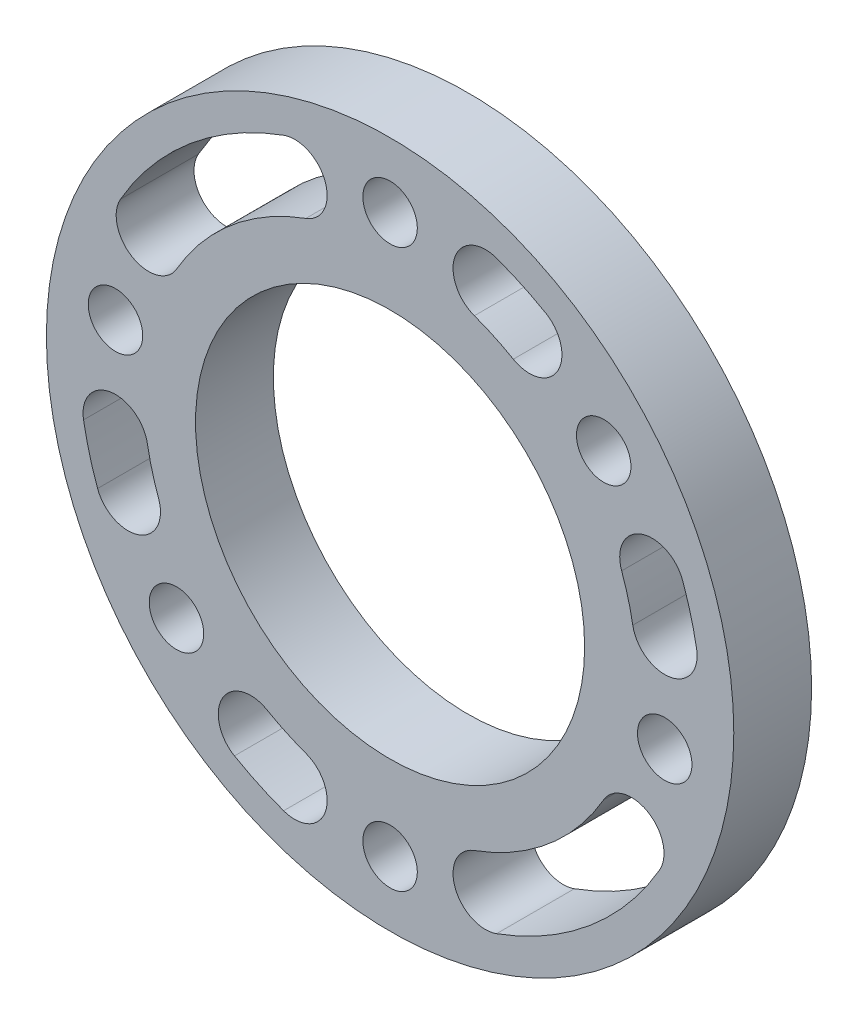
SolidWorks part; units mm, degrees
material "6061 合金"
ref_plane "前视基准面" through (0, 0, 0) normal (0, 0, 1) x (1, 0, 0)
ref_plane "上视基准面" through (0, 0, 0) normal (0, 1, 0) x (1, 0, 0)
ref_plane "右视基准面" through (0, 0, 0) normal (1, 0, 0) x (0, 0, -1)
sketch "草图1" plane through (0, 0, 0) normal (0, 0, 1) x (1, 0, 0)
  circle A0 centre (0, 0) radius 15
  circle A1 centre (0, 0) radius 26.5
  circle A2 centre (0, 0) radius 21.5 construction
  circle A3 centre (0, 21.5) radius 2.1
  circle A4 centre (16.47, 13.8199) radius 2.1
  circle A5 centre (21.1734, -3.7334) radius 2.1
  circle A6 centre (0, -21.5) radius 2.1
  circle A7 centre (-16.47, -13.8199) radius 2.1
  circle A8 centre (-21.1734, 3.7334) radius 2.1
  arc A9 (-18.6195, 10.75) -> (-7.3534, 20.2034) centre (0, 0) cw construction
  arc A10 (-8.2085, 22.5526) -> (-20.7846, 12) centre (0, 0) ccw
  arc A11 (-6.4984, 17.8542) -> (-16.4545, 9.5) centre (0, 0) ccw
  arc A12 (-6.4984, 17.8542) -> (-8.2085, 22.5526) centre (-7.3534, 20.2034) ccw
  arc A13 (-20.7846, 12) -> (-16.4545, 9.5) centre (-18.6195, 10.75) ccw
  arc A14 (7.3534, 20.2034) -> (10.75, 18.6195) centre (0, 0) cw construction
  arc A15 (12, 20.7846) -> (8.2085, 22.5526) centre (0, 0) ccw
  arc A16 (9.5, 16.4545) -> (6.4984, 17.8542) centre (0, 0) ccw
  arc A17 (9.5, 16.4545) -> (12, 20.7846) centre (10.75, 18.6195) ccw
  arc A18 (8.2085, 22.5526) -> (6.4984, 17.8542) centre (7.3534, 20.2034) ccw
  arc A19 (18.7113, 3.2993) -> (17.8542, 6.4984) centre (0, 0) ccw
  arc A20 (18.7113, 3.2993) -> (23.6354, 4.1676) centre (21.1734, 3.7334) ccw
  arc A21 (22.5526, 8.2085) -> (17.8542, 6.4984) centre (20.2034, 7.3534) ccw
  arc A22 (23.6354, 4.1676) -> (22.5526, 8.2085) centre (0, 0) ccw
  arc A23 (20.2034, 7.3534) -> (21.1734, 3.7334) centre (0, 0) cw construction
  arc A24 (6.4984, -17.8542) -> (16.4545, -9.5) centre (0, 0) ccw
  arc A25 (6.4984, -17.8542) -> (8.2085, -22.5526) centre (7.3534, -20.2034) ccw
  arc A26 (20.7846, -12) -> (16.4545, -9.5) centre (18.6195, -10.75) ccw
  arc A27 (8.2085, -22.5526) -> (20.7846, -12) centre (0, 0) ccw
  arc A28 (-9.5, -16.4545) -> (-6.4984, -17.8542) centre (0, 0) ccw
  arc A29 (-9.5, -16.4545) -> (-12, -20.7846) centre (-10.75, -18.6195) ccw
  arc A30 (-8.2085, -22.5526) -> (-6.4984, -17.8542) centre (-7.3534, -20.2034) ccw
  arc A31 (-12, -20.7846) -> (-8.2085, -22.5526) centre (0, 0) ccw
  arc A32 (-23.6354, -4.1676) -> (-22.5526, -8.2085) centre (0, 0) ccw
  arc A33 (-22.5526, -8.2085) -> (-17.8542, -6.4984) centre (-20.2034, -7.3534) ccw
  arc A34 (-18.7113, -3.2993) -> (-17.8542, -6.4984) centre (0, 0) ccw
  arc A35 (-18.7113, -3.2993) -> (-23.6354, -4.1676) centre (-21.1734, -3.7334) ccw
  arc A36 (18.6195, -10.75) -> (7.3534, -20.2034) centre (0, 0) cw construction
  arc A37 (-7.3534, -20.2034) -> (-10.75, -18.6195) centre (0, 0) cw construction
  arc A38 (-20.2034, -7.3534) -> (-21.1734, -3.7334) centre (0, 0) cw construction
  point P9 (-13.8199, 16.47)
  point P27 (9.0863, 19.4856)
  point P36 (20.7674, 5.5646)
  point P44 (13.8199, -16.47)
  point P51 (-9.0863, -19.4856)
  point P58 (-20.7674, -5.5646)
  dimension "D1" = 30
  dimension "D2" = 53
  dimension "D3" = 43
  dimension "D4" = 4.2
  dimension "D8" = 2.5
  dimension "D11" = 20
  dimension "D6" = 50
  dimension "D9" = 20
  dimension "D10" = 20
  dimension "D12" = 20
  dimension "D13" = 2
  dimension "D14" = 20
  dimension "D5" = 3
  dimension "D7" = 2
  dimension "D15" = 2
extrude "凸台-拉伸1" add sketch "草图1" along normal blind 6
